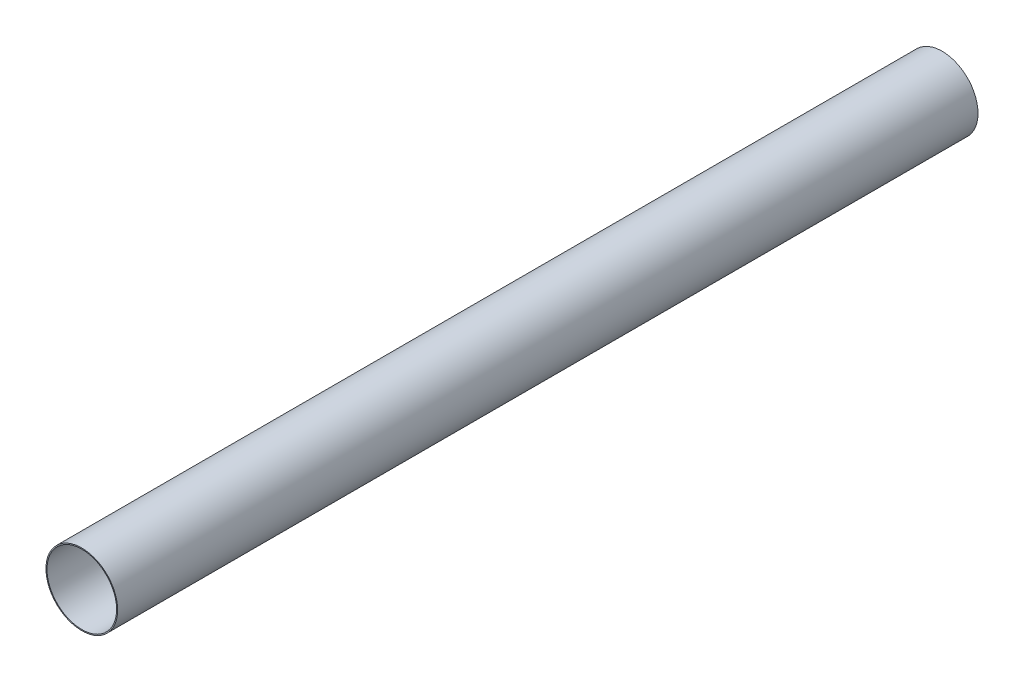
SolidWorks part; units mm, degrees
ref_plane "Front Plane" through (0, 0, 0) normal (0, 0, 1) x (1, 0, 0)
ref_plane "Top Plane" through (0, 0, 0) normal (0, 1, 0) x (1, 0, 0)
ref_plane "Right Plane" through (0, 0, 0) normal (1, 0, 0) x (0, 0, -1)
sketch "Sketch1" plane through (0, 0, 0) normal (0, 0, 1) x (1, 0, 0)
  circle A0 centre (0, 0) radius 69.85
  circle A1 centre (0, 0) radius 67.85
  dimension "D1" = 2
  dimension "D2" = 139.7
extrude "Boss-Extrude1" add sketch "Sketch1" along normal blind 1676.4
